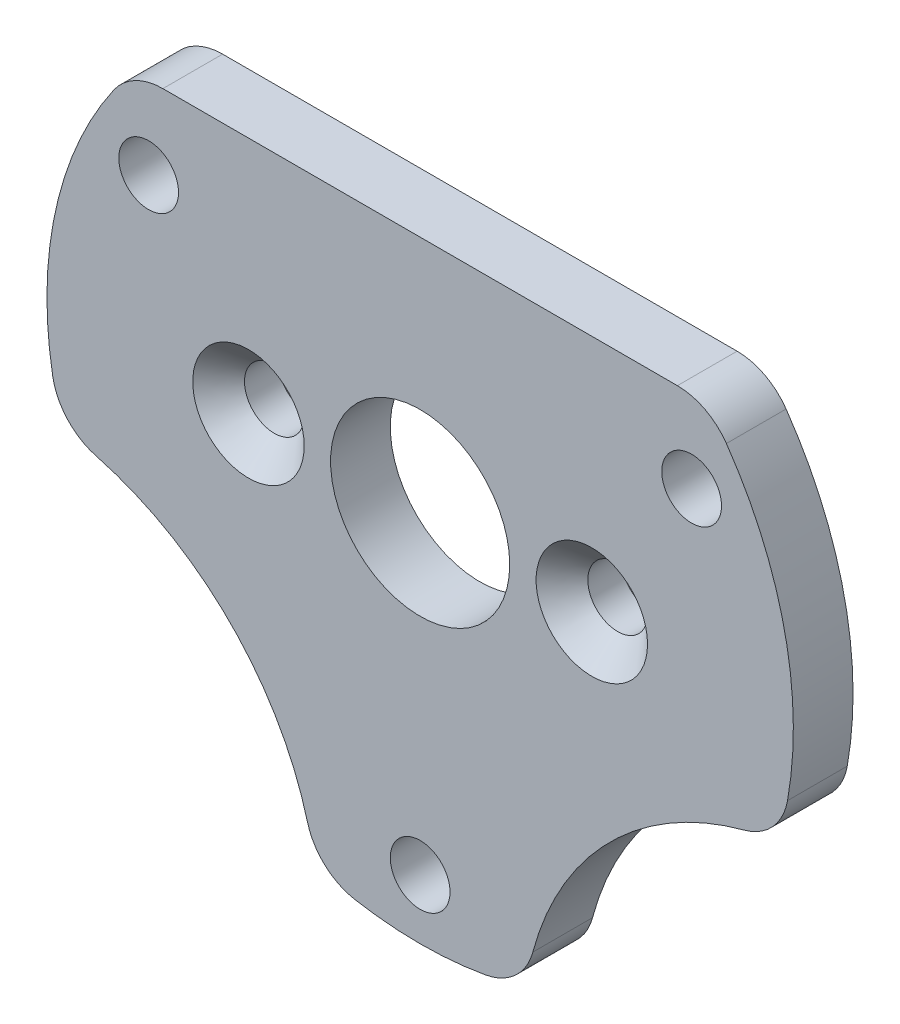
SolidWorks part; units mm, degrees
material "Thornel Mat VMA"
ref_plane "前视基准面" through (0, 0, 0) normal (0, 0, 1) x (1, 0, 0)
ref_plane "上视基准面" through (0, 0, 0) normal (0, 1, 0) x (1, 0, 0)
ref_plane "右视基准面" through (0, 0, 0) normal (1, 0, 0) x (0, 0, -1)
sketch "草图1" plane through (0, 0, 0) normal (0, 0, 1) x (1, 0, 0)
  line L0 (0, 0) -> (0, 24.8867) construction
  line L1 (-9.6047, 8) -> (9.6047, 8)
  line L2 (0, 0) -> (0, -15.4904) construction
  line L3 (-12.5, 0) -> (12.5, 0) construction
  arc A0 (-9.6047, 8) -> (9.6047, 8) centre (0, 0) ccw
  circle A1 centre (0, 0) radius 10.5 construction
  circle A2 centre (0, -10.5) radius 1
  circle A3 centre (-9.0933, 5.25) radius 1
  circle A4 centre (9.0933, 5.25) radius 1
  circle A5 centre (-5.75, 0) radius 1
  circle A6 centre (5.75, 0) radius 1
  circle A7 centre (0, 0) radius 3
  point P16 (0, 0)
  dimension "D1" = 12.5
  dimension "D3" = 21
  dimension "D4" = 2
  dimension "D6" = 2
  dimension "D8" = 6
  dimension "D2" = 8
  dimension "D7" = 11.5
  dimension "D5" = 3
extrude "凸台-拉伸1" add sketch "草图1" along normal blind 2
sketch "草图2" plane through (0, 0, 2) normal (0, 0, 1) x (1, 0, 0)
  line L0 (0, 0) -> (-12.6952, -12.6952) construction
  line L1 (0, 0) -> (0, -17.9956) construction
  arc A0 (-11.9882, -3.5402) -> (-3.5402, -11.9882) centre (-13.435, -13.435) cw
  arc A1 (-9.6047, 8) -> (9.6047, 8) centre (0, 0) ccw construction
  arc A2 (-11.9882, -3.5402) -> (-3.5402, -11.9882) centre (0, 0) ccw
  arc A3 (11.9882, -3.5402) -> (3.5402, -11.9882) centre (13.435, -13.435) ccw
  arc A4 (11.9882, -3.5402) -> (3.5402, -11.9882) centre (0, 0) cw
  dimension "D2" = 10
  dimension "D1" = 45
  dimension "D3" = 19
extrude "切除-拉伸1" cut sketch "草图2" against normal blind 10
fillet "圆角1" radius 2 6 edges at (-9.6047, 8, 1) (9.6047, 8, 1) (11.9882, -3.5402, 1) (3.5402, -11.9882, 1) (-3.5402, -11.9882, 1) (-11.9882, -3.5402, 1)
chamfer "倒角1" distance 0.866 angle 45 2 edges at (4.75, 0, 2) (-4.75, 0, 2)
